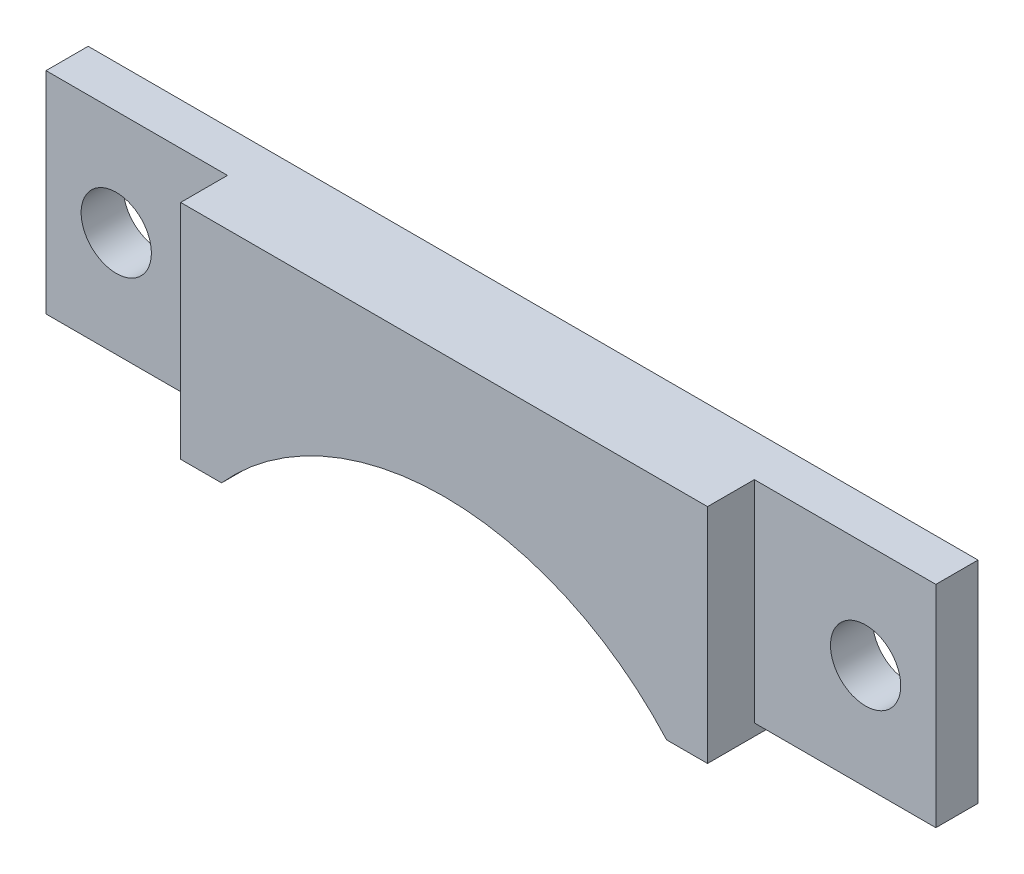
SolidWorks part; units mm, degrees
material "ABS"
ref_plane "前视基准面" through (0, 0, 0) normal (0, 0, 1) x (1, 0, 0)
ref_plane "上视基准面" through (0, 0, 0) normal (0, 1, 0) x (1, 0, 0)
ref_plane "右视基准面" through (0, 0, 0) normal (1, 0, 0) x (0, 0, -1)
sketch "草图1" plane through (0, 0, 0) normal (0, 0, 1) x (1, 0, 0)
  line L0 (-9.5033, -4.75) -> (-19, -4.75)
  line L1 (19, 4.75) -> (-19, 4.75)
  line L2 (19, 4.75) -> (19, -4.75)
  line L3 (19, -4.75) -> (9.5033, -4.75)
  line L4 (-19, 4.75) -> (-19, -4.75)
  line L5 (0, -4.75) -> (0, 4.75) construction
  line L6 (19, 0) -> (-19, 0) construction
  arc A0 (9.5033, -4.75) -> (-9.5033, -4.75) centre (0, -13.25) ccw
  circle A1 centre (-16, 0.25) radius 1.5
  circle A2 centre (16, 0.25) radius 1.5
  point P0 (0, 0)
  dimension "D3" = 25.5
  dimension "D6" = 3
  dimension "D1" = 38
  dimension "D2" = 8.5
  dimension "D4" = 9.5
  dimension "D5" = 5
  dimension "D7" = 3
extrude "凸台-拉伸1" add sketch "草图1" along normal blind 1.8
sketch "草图2" plane through (0, 0, 1.8) normal (0, 0, 1) x (1, 0, 0)
  line L0 (-11.25, -4.75) -> (-11.25, 4.75)
  line L1 (-19, -4.75) -> (-9.5033, -4.75) construction
  line L2 (19, 4.75) -> (-19, 4.75) construction
  line L3 (-11.25, 4.75) -> (11.25, 4.75)
  line L4 (11.25, 4.75) -> (11.25, -4.75)
  line L5 (9.5033, -4.75) -> (19, -4.75) construction
  line L6 (-9.5033, -4.75) -> (-11.25, -4.75)
  line L7 (9.5033, -4.75) -> (11.25, -4.75)
  line L8 (11.25, -4.75) -> (11.2836, -4.8718)
  arc A0 (9.5033, -4.75) -> (-9.5033, -4.75) centre (0, -13.25) ccw construction
  arc A1 (9.5033, -4.75) -> (-9.5033, -4.75) centre (0, -13.25) ccw
  line M5 (-19, -4.75) -> (-9.5033, -4.75)
  arc M6 (-9.5033, -4.75) -> (9.5033, -4.75) centre (0, -13.25) cw
  line M7 (9.5033, -4.75) -> (19, -4.75)
  line M9 (19, 4.75) -> (-19, 4.75)
  dimension "D1" = 22.5
  dimension "D2" = 11.25
extrude "凸台-拉伸2" add sketch "草图2" along normal blind 2 contours L4 L0 M9 M5 M6 M7
sketch "草图3" plane through (0, 0, 1.8) normal (0, 0, 1) x (1, 0, 0)
  line L0 (-11.25, -4.25) -> (-19, -4.25)
  line L1 (-11.25, -4.75) -> (-11.25, 4.75) construction
  line L2 (-19, 4.75) -> (-19, -4.75) construction
  line L3 (-19, -4.25) -> (-19, -4.75)
  line L4 (-19, -4.75) -> (-11.25, -4.75)
  line L5 (-11.25, -4.75) -> (-11.25, -4.25)
  line L6 (0, 9.7063) -> (0, -10.1521) construction
  line L7 (11.25, -4.75) -> (11.25, -4.25)
  line L8 (19, -4.75) -> (11.25, -4.75)
  line L9 (19, -4.25) -> (19, -4.75)
  line L10 (11.25, -4.25) -> (19, -4.25)
  dimension "D1" = 0.5
extrude "切除-拉伸1" cut sketch "草图3" against normal through all
